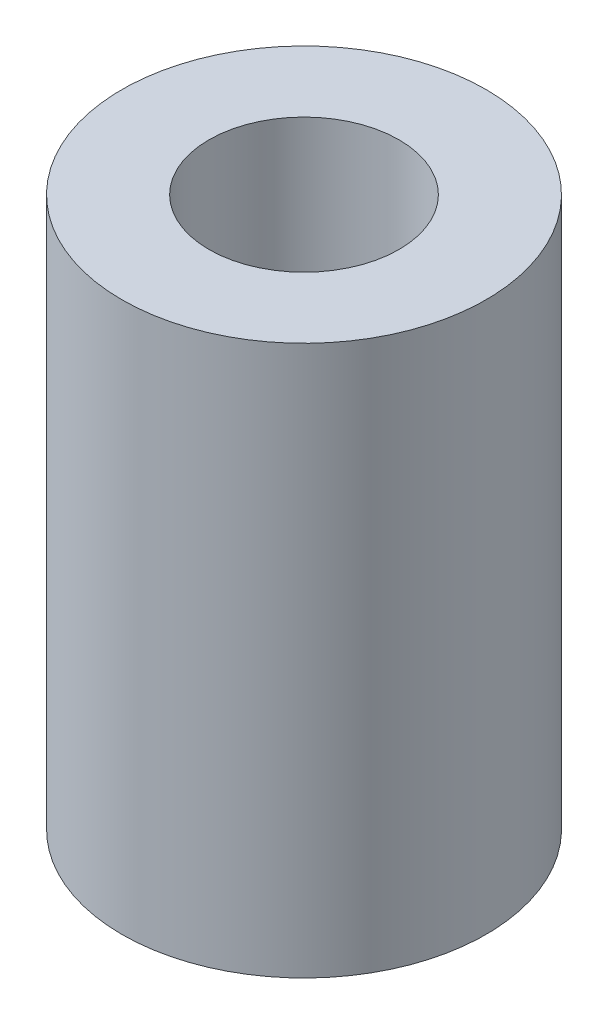
SolidWorks part; units mm, degrees
ref_plane "Front Plane" through (0, 0, 0) normal (0, 0, 1) x (1, 0, 0)
ref_plane "Top Plane" through (0, 0, 0) normal (0, 1, 0) x (1, 0, 0)
ref_plane "Right Plane" through (0, 0, 0) normal (1, 0, 0) x (0, 0, -1)
sketch "Sketch1" plane through (0, 0, 0) normal (0, 1, 0) x (1, 0, 0)
  circle A0 centre (0, 0) radius 2.075
  circle A1 centre (0, 0) radius 3.975
  dimension "D1" = 7.95
  dimension "D2" = 4.15
extrude "Boss-Extrude1" add sketch "Sketch1" along normal blind 12
